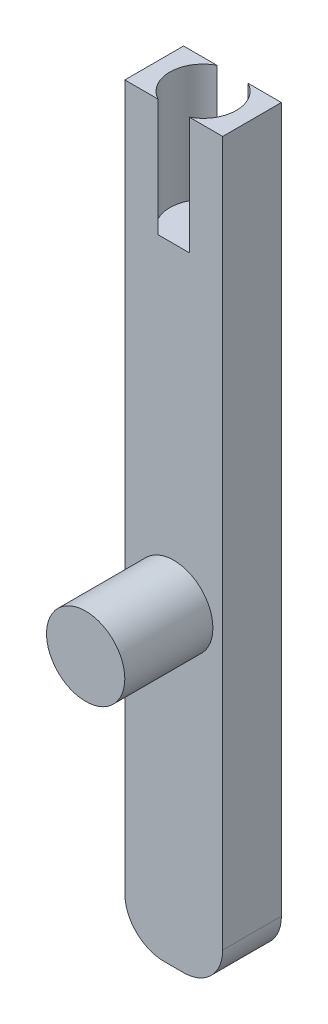
SolidWorks part; units mm, degrees
ref_plane "Спереди" through (0, 0, 0) normal (0, 0, 1) x (1, 0, 0)
ref_plane "Сверху" through (0, 0, 0) normal (0, 1, 0) x (1, 0, 0)
ref_plane "Справа" through (0, 0, 0) normal (1, 0, 0) x (0, 0, -1)
sketch "Эскиз1" plane through (0, 0, 0) normal (0, 0, 1) x (1, 0, 0)
  line L1 (-1, 0) -> (-1.5, 0)
  line L2 (0, 1) -> (0, 19)
  line L3 (0, 19) -> (-2.5, 19)
  line L4 (-2.5, 1) -> (-2.5, 19)
  arc A0 (-1, 0) -> (0, 1) centre (-1, 1) ccw
  arc A1 (-1.5, 0) -> (-2.5, 1) centre (-1.5, 1) cw
  point P7 (0, 0)
  point P10 (-2.5, 0)
  dimension "D3" = 1
  dimension "D1" = 19
  dimension "D2" = 2.5
extrude "Бобышка-Вытянуть1" add sketch "Эскиз1" along normal blind 1.5
sketch "Эскиз2" plane through (0, 0, 1.5) normal (0, 0, 1) x (1, 0, 0)
  line L0 (-1.25, 19) -> (-1.25, 8) construction
  line L1 (0, 19) -> (-2.5, 19) construction
  circle A0 centre (-1.25, 8) radius 1
  dimension "D2" = 2
  dimension "D1" = 11
extrude "Бобышка-Вытянуть2" add sketch "Эскиз2" along normal blind 2.25
sketch "Эскиз3" plane through (0, 19, 0) normal (0, 1, 0) x (1, 0, 0)
  line L0 (-2.5, -1.5) -> (0, 0) construction
  circle A0 centre (-1.25, -0.75) radius 0.85
  dimension "D1" = 1.7
extrude "Вырез-Вытянуть1" cut sketch "Эскиз3" against normal blind 3
